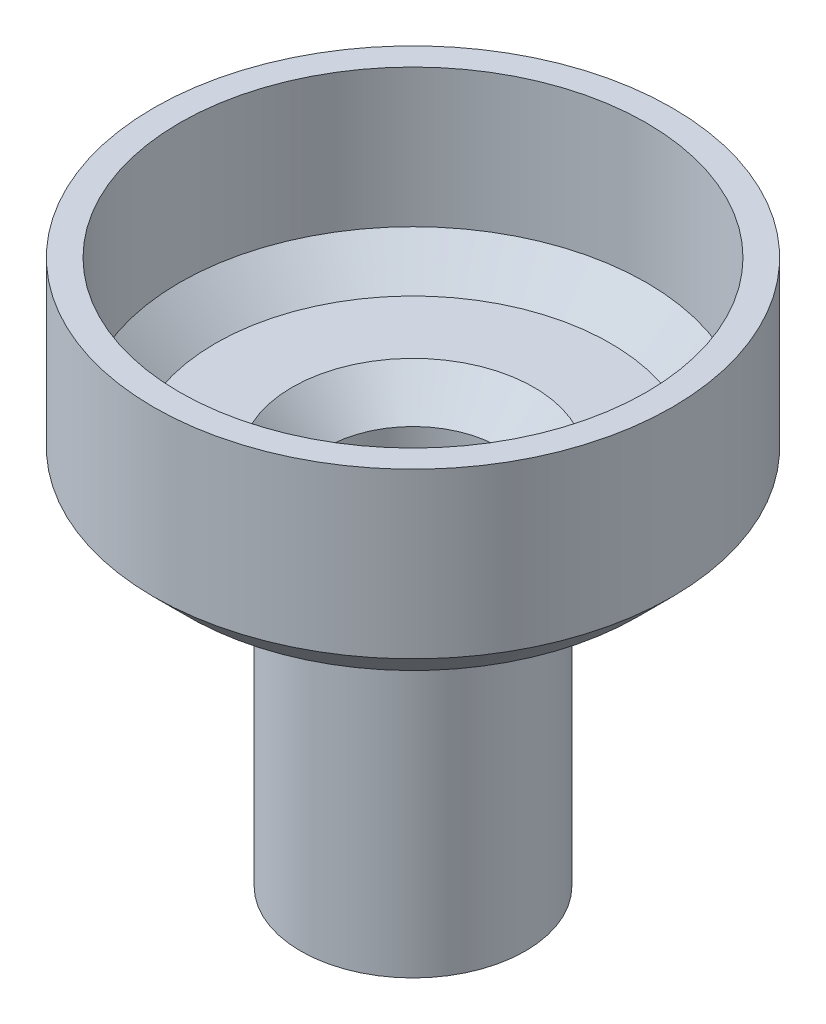
SolidWorks part; units mm, degrees
ref_plane "前视基准面" through (0, 0, 0) normal (0, 0, 1) x (1, 0, 0)
ref_plane "上视基准面" through (0, 0, 0) normal (0, 1, 0) x (1, 0, 0)
ref_plane "右视基准面" through (0, 0, 0) normal (1, 0, 0) x (0, 0, -1)
other "Configuration Table"
sketch "草图1" plane through (0, 0, 0) normal (0, 0, 1) x (1, 0, 0)
  line L0 (0, -297.3267) -> (0, 14569.0093) construction
  line L1 (5, 0) -> (5, 18.5) construction
  line L2 (0, 0) -> (5, 0)
  line L3 (0, 0) -> (0, -1.5)
  line L4 (0, -1.5) -> (5, -1.5)
  line L5 (5, 0) -> (5, -1.5) construction
  line L6 (5, -1.5) -> (6.5, -1.5)
  line L7 (5, -1.5) -> (5, 18.5) construction
  line L8 (5, 18.5) -> (6.5, 18.5) construction
  line L9 (6.5, -1.5) -> (6.5, 18.5) construction
  line L10 (5, 18.5) -> (15, 18.5) construction
  line L11 (5, 18.5) -> (5, 20) construction
  line L12 (5, 20) -> (15, 20) construction
  line L13 (15, 18.5) -> (15, 20) construction
  line L14 (15, 20) -> (13.5, 20) construction
  line L15 (15, 20) -> (15, 30) construction
  line L16 (15, 30) -> (13.5, 30)
  line L17 (13.5, 20) -> (13.5, 30) construction
  line L18 (5, 20) -> (13.5, 20) construction
  line L19 (6.5, 18.5) -> (15, 18.5) construction
  line L20 (13.5, 22) -> (11.4186, 20)
  line L21 (13.5, 22) -> (13.5, 30)
  line L22 (5, 20) -> (11.4186, 20) construction
  line L23 (15, 20.5) -> (13, 18.5)
  line L24 (6.5, 18.5) -> (13, 18.5) construction
  line L25 (15, 20.5) -> (15, 30)
  line L26 (8.5, 18.5) -> (6.5, 16.5)
  line L27 (7, 20) -> (5, 18)
  line L28 (7, 20) -> (11.4186, 20)
  line L29 (13, 18.5) -> (8.5, 18.5)
  line L30 (6.5, 16.5) -> (6.5, -1.5)
  line L31 (5, 0) -> (5, 18)
  dimension "D9" = 2
  dimension "D10" = 2.0814
  dimension "D1" = 5
  dimension "D2" = 1.5
  dimension "D3" = 1.5
  dimension "D4" = 1.5
  dimension "D5" = 20
  dimension "D6" = 15
  dimension "D7" = 1.5
  dimension "D8" = 10
  dimension "D11" = 2
  dimension "D12" = 2
  dimension "D13" = 2
  dimension "D14" = 2
  dimension "D15" = 2
  dimension "D16" = 2
revolve "旋转3" add sketch "草图1" angle 360 about L0
sketch "草图2" plane through (0, 0, 0) normal (0, 1, 0) x (1, 0, 0)
  circle A0 centre (0, 0) radius 2
  dimension "D1" = 4
extrude "切除-拉伸1" cut sketch "草图2" against normal up to surface (1.5 mm away) from surface at 0 up to face at (6.5, -1.5, 0) starting at face at (5, 0, 0)
